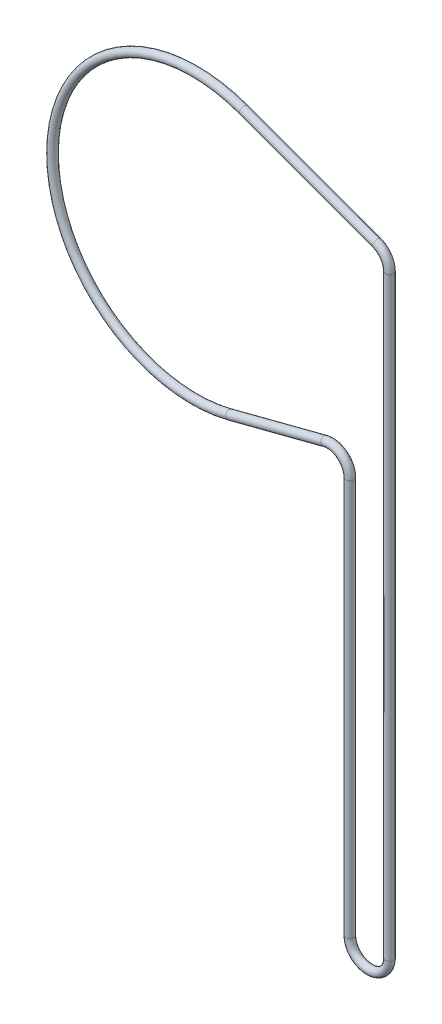
SolidWorks part; units mm, degrees
ref_plane "Plan de face" through (0, 0, 0) normal (0, 0, 1) x (1, 0, 0)
ref_plane "Plan de dessus" through (0, 0, 0) normal (0, 1, 0) x (1, 0, 0)
ref_plane "Plan de droite" through (0, 0, 0) normal (1, 0, 0) x (0, 0, -1)
sketch "Esquisse1" plane through (0, 0, 0) normal (0, 1, 0) x (1, 0, 0)
  circle A0 centre (0, 0) radius 1.25
  dimension "D1" = 2.5
sketch "Esquisse2" plane through (0, 0, 0) normal (0, 0, 1) x (1, 0, 0)
  line L0 (0, 0) -> (0, 180)
  line L1 (-3.9375, 185.6344) -> (-44.2187, 200.3796)
  line L2 (-48.2217, 118.3727) -> (-19.5039, 125.8085)
  line L3 (-12, 120) -> (-12, 0)
  arc A0 (0, 180) -> (-3.9375, 185.6344) centre (-6, 180) ccw
  arc A1 (-44.2187, 200.3796) -> (-48.2217, 118.3727) centre (-59, 160) ccw
  arc A2 (-19.5039, 125.8085) -> (-12, 120) centre (-18, 120) cw
  arc A3 (-12, 0) -> (0, 0) centre (-6, 0) ccw
  dimension "D1" = 6
  dimension "D2" = 180
  dimension "D3" = 43
  dimension "D4" = 53
  dimension "D5" = 40
  dimension "D6" = 12
  dimension "D7" = 160
sweep "Balayage1" add profiles "Esquisse1" path "Esquisse2"
